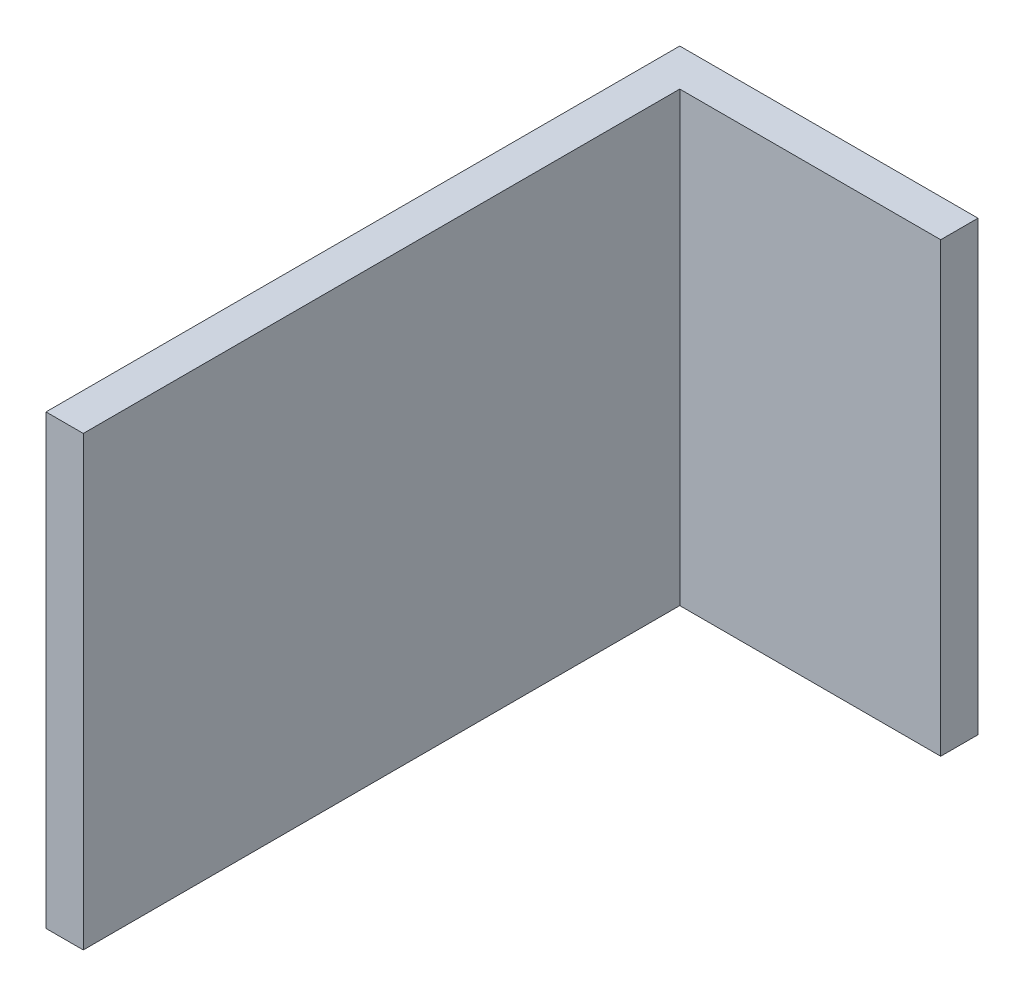
SolidWorks part; units mm, degrees
material "ABS"
ref_plane "Front Plane" through (0, 0, 0) normal (0, 0, 1) x (1, 0, 0)
ref_plane "Top Plane" through (0, 0, 0) normal (0, 1, 0) x (1, 0, 0)
ref_plane "Right Plane" through (0, 0, 0) normal (1, 0, 0) x (0, 0, -1)
sketch "Sketch1" plane through (0, 0, 0) normal (0, 0, 1) x (1, 0, 0)
  line L1 (0, 0) -> (25.4, 0)
  line L2 (0, 0) -> (0, 38.1)
  line L3 (0, 38.1) -> (25.4, 38.1)
  line L4 (25.4, 0) -> (25.4, 38.1)
  dimension "D1" = 25.4
  dimension "D2" = 38.1
extrude "Boss-Extrude1" add sketch "Sketch1" along normal blind 3.175
sketch "Sketch2" plane through (0, 0, 3.175) normal (0, 0, 1) x (1, 0, 0)
  line L0 (0, 0) -> (25.4, 0) construction
  line L1 (0, 38.1) -> (3.175, 38.1)
  line L2 (0, 38.1) -> (0, 0)
  line L3 (0, 0) -> (3.175, 0)
  line L4 (3.175, 38.1) -> (3.175, 0)
  dimension "D1" = 3.175
extrude "Boss-Extrude2" add sketch "Sketch2" along normal blind 50.8
